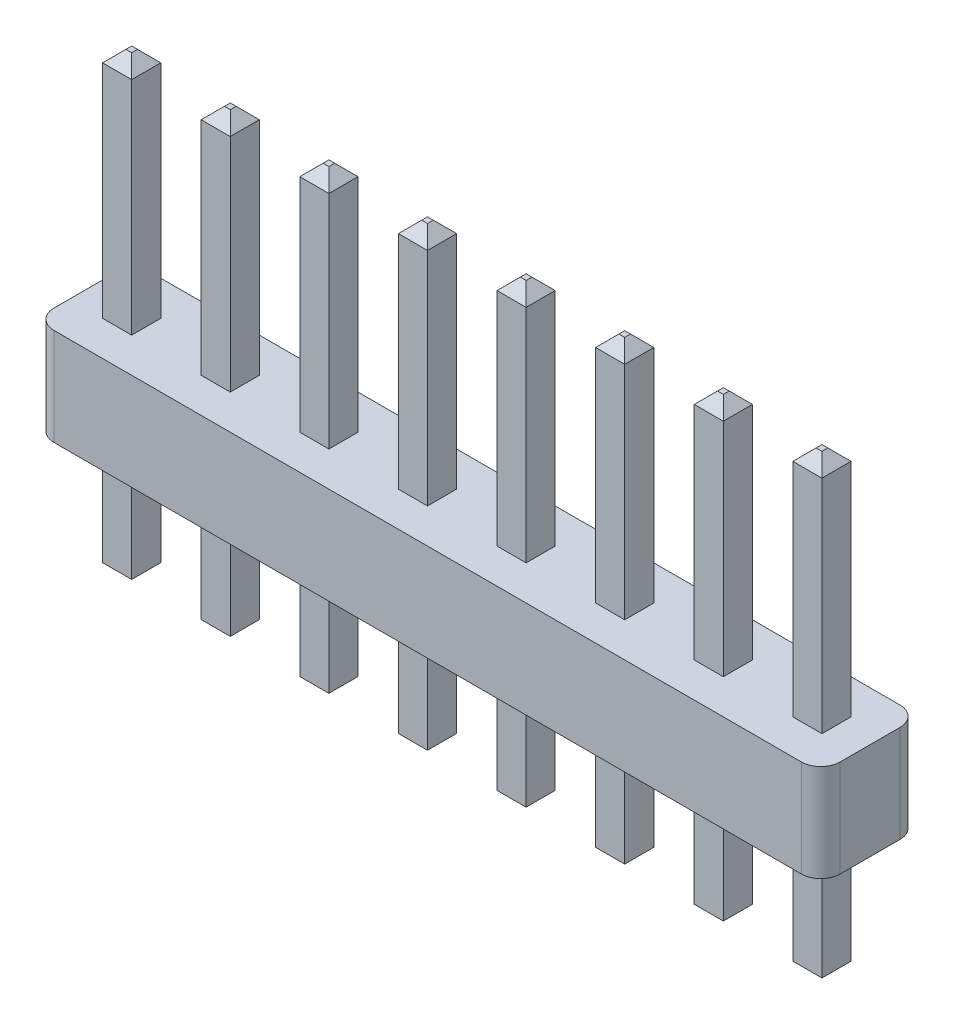
SolidWorks part; units mm, degrees
ref_plane "Front Plane" through (0, 0, 0) normal (0, 0, 1) x (1, 0, 0)
ref_plane "Top Plane" through (0, 0, 0) normal (0, 1, 0) x (1, 0, 0)
ref_plane "Right Plane" through (0, 0, 0) normal (1, 0, 0) x (0, 0, -1)
ref_plane "Plane1" through (0, 0, 0) normal (0, 1, 0) x (-1, 0, 0)
sketch "Sketch1" plane through (0, 0, 0) normal (0, 1, 0) x (-1, 0, 0)
  line L0 (-17.25, 1.27) -> (2, 1.27)
  line L1 (2.5, 0.77) -> (2.5, -0.77)
  line L2 (2, -1.27) -> (-17.25, -1.27)
  line L3 (-17.75, -0.77) -> (-17.75, 0.77)
  line L4 (0, 55) -> (0, -55) construction
  line L5 (55, 0) -> (-55, 0) construction
  arc A0 (2.5, 0.77) -> (2, 1.27) centre (2, 0.77) ccw
  arc A1 (2, -1.27) -> (2.5, -0.77) centre (2, -0.77) ccw
  arc A2 (-17.75, -0.77) -> (-17.25, -1.27) centre (-17.25, -0.77) ccw
  arc A3 (-17.25, 1.27) -> (-17.75, 0.77) centre (-17.25, 0.77) ccw
  dimension "D5" = 0.5
  dimension "D1" = 20.25
  dimension "D2" = 2.54
  dimension "D3" = 2.5
  dimension "D4" = 1.27
extrude "Boss-Extrude1" add sketch "Sketch1" along normal blind 2.5
ref_plane "Plane2" through (0, 0, 0) normal (0, 1, 0) x (-1, 0, 0)
sketch "Sketch2" plane through (0, 0, 0) normal (0, 1, 0) x (-1, 0, 0)
  line L0 (0.895, 0.375) -> (1.645, 0.375)
  line L1 (1.645, 0.375) -> (1.645, -0.375)
  line L2 (1.645, -0.375) -> (0.895, -0.375)
  line L3 (0.895, -0.375) -> (0.895, 0.375)
  line L4 (-0.895, -0.375) -> (-1.645, -0.375)
  line L5 (-1.645, -0.375) -> (-1.645, 0.375)
  line L6 (-1.645, 0.375) -> (-0.895, 0.375)
  line L7 (-0.895, 0.375) -> (-0.895, -0.375)
  line L8 (-1.645, 0.375) -> (-0.895, -0.375) construction
  line L9 (0.895, -0.375) -> (1.645, 0.375) construction
  line L10 (1.375, 0) -> (-1.375, 0) construction
  line L11 (0, 1.375) -> (0, -1.375) construction
  line L12 (-4.185, 0.375) -> (-3.435, 0.375)
  line L13 (-3.435, 0.375) -> (-3.435, -0.375)
  line L14 (-3.435, -0.375) -> (-4.185, -0.375)
  line L15 (-4.185, -0.375) -> (-4.185, 0.375)
  line L16 (-5.975, -0.375) -> (-6.725, -0.375)
  line L17 (-6.725, -0.375) -> (-6.725, 0.375)
  line L18 (-6.725, 0.375) -> (-5.975, 0.375)
  line L19 (-5.975, 0.375) -> (-5.975, -0.375)
  line L20 (-6.725, 0.375) -> (-5.975, -0.375) construction
  line L21 (-4.185, -0.375) -> (-3.435, 0.375) construction
  line L22 (-9.265, 0.375) -> (-8.515, 0.375)
  line L23 (-8.515, 0.375) -> (-8.515, -0.375)
  line L24 (-8.515, -0.375) -> (-9.265, -0.375)
  line L25 (-9.265, -0.375) -> (-9.265, 0.375)
  line L26 (-11.055, -0.375) -> (-11.805, -0.375)
  line L27 (-11.805, -0.375) -> (-11.805, 0.375)
  line L28 (-11.805, 0.375) -> (-11.055, 0.375)
  line L29 (-11.055, 0.375) -> (-11.055, -0.375)
  line L30 (-11.805, 0.375) -> (-11.055, -0.375) construction
  line L31 (-9.265, -0.375) -> (-8.515, 0.375) construction
  line L32 (-14.345, 0.375) -> (-13.595, 0.375)
  line L33 (-13.595, 0.375) -> (-13.595, -0.375)
  line L34 (-13.595, -0.375) -> (-14.345, -0.375)
  line L35 (-14.345, -0.375) -> (-14.345, 0.375)
  line L36 (-16.135, -0.375) -> (-16.885, -0.375)
  line L37 (-16.885, -0.375) -> (-16.885, 0.375)
  line L38 (-16.885, 0.375) -> (-16.135, 0.375)
  line L39 (-16.135, 0.375) -> (-16.135, -0.375)
  line L40 (-16.885, 0.375) -> (-16.135, -0.375) construction
  line L41 (-14.345, -0.375) -> (-13.595, 0.375) construction
  point P8 (-1.27, 0)
  point P9 (1.27, 0)
  point P23 (-6.35, 0)
  point P24 (-3.81, 0)
  point P33 (-11.43, 0)
  point P34 (-8.89, 0)
  point P43 (-16.51, 0)
  point P44 (-13.97, 0)
  dimension "D1" = 2.54
  dimension "D2" = 0.75
  dimension "D3" = 1.27
  dimension "D4" = 4
extrude "Boss-Extrude2" add sketch "Sketch2" along normal blind 8.5 and the other way blind 3.25
chamfer "Chamfer1" distance 0.3 angle 45 64 edges at (-1.645, 8.5, 0) (-1.27, 8.5, -0.375) (-0.895, 8.5, 0) (-1.27, 8.5, 0.375) (0.895, 8.5, 0) (1.27, 8.5, -0.375) (1.645, 8.5, 0) (1.27, 8.5, 0.375) (1.27, -3.25, -0.375) (1.645, -3.25, 0) (0.895, -3.25, 0) (1.27, -3.25, 0.375) (-1.27, -3.25, 0.375) (-1.645, -3.25, 0) (-0.895, -3.25, 0) (-1.27, -3.25, -0.375) (16.51, 8.5, -0.375) (16.885, 8.5, 0) (16.51, 8.5, 0.375) (16.135, 8.5, 0) (13.97, 8.5, 0.375) (13.595, 8.5, 0) (13.97, 8.5, -0.375) (14.345, 8.5, 0) (11.43, 8.5, -0.375) (11.805, 8.5, 0) (11.43, 8.5, 0.375) (11.055, 8.5, 0) (8.89, 8.5, 0.375) (8.515, 8.5, 0) (8.89, 8.5, -0.375) (9.265, 8.5, 0) (6.35, 8.5, -0.375) (6.725, 8.5, 0) (6.35, 8.5, 0.375) (5.975, 8.5, 0) (3.81, 8.5, 0.375) (3.435, 8.5, 0) (3.81, 8.5, -0.375) (4.185, 8.5, 0) (3.81, -3.25, -0.375) (3.435, -3.25, 0) (3.81, -3.25, 0.375) (4.185, -3.25, 0) (6.35, -3.25, 0.375) (6.725, -3.25, 0) (6.35, -3.25, -0.375) (5.975, -3.25, 0) (8.89, -3.25, -0.375) (8.515, -3.25, 0) (8.89, -3.25, 0.375) (9.265, -3.25, 0) (11.43, -3.25, 0.375) (11.805, -3.25, 0) (11.43, -3.25, -0.375) (11.055, -3.25, 0) (13.97, -3.25, -0.375) (13.595, -3.25, 0) (13.97, -3.25, 0.375) (14.345, -3.25, 0) (16.51, -3.25, 0.375) (16.885, -3.25, 0) (16.51, -3.25, -0.375) (16.135, -3.25, 0)
